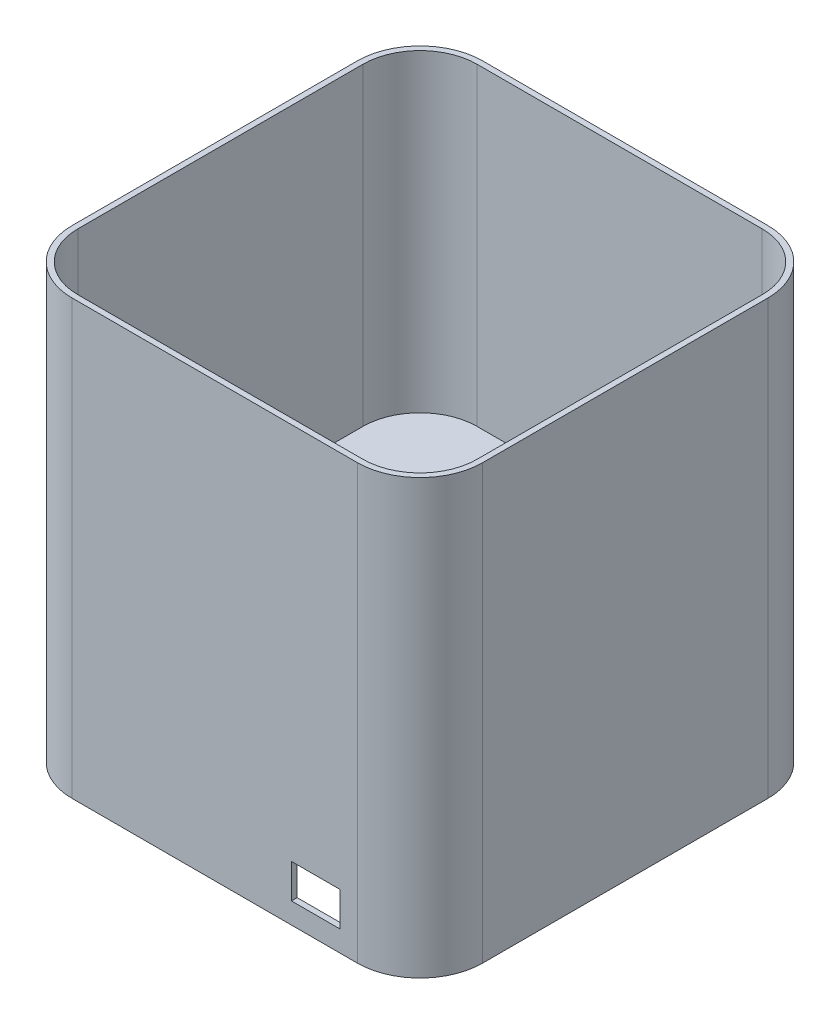
SolidWorks part; units mm, degrees
ref_plane "Plan de face" through (0, 0, 0) normal (0, 0, 1) x (1, 0, 0)
ref_plane "Plan de dessus" through (0, 0, 0) normal (0, 1, 0) x (1, 0, 0)
ref_plane "Plan de droite" through (0, 0, 0) normal (1, 0, 0) x (0, 0, -1)
sketch "Esquisse1" plane through (0, 0, 0) normal (0, 1, 0) x (1, 0, 0)
  line L30 (-70, -70) -> (70, -70)
  line L31 (-70, -70) -> (-70, 70)
  line L32 (-70, 70) -> (70, 70)
  line L33 (70, -70) -> (70, 70)
  line L34 (-70, -70) -> (70, 70) construction
  line L35 (-70, 70) -> (70, -70) construction
  point P0 (0, 0)
  dimension "D1" = 140
  dimension "D2" = 140
extrude "Boss.-Extru.1" add sketch "Esquisse1" along normal blind 150
fillet "Congé1" radius 20 4 edges at (70, 75, 70) (-70, 75, 70) (-70, 75, -70) (70, 75, -70)
shell "Coque1" thickness 2
sketch "Esquisse2" plane through (0, 0, 0) normal (0, 1, 0) x (1, 0, 0)
  line L4 (70, -50) -> (70, 50)
  line L5 (50, 70) -> (-50, 70)
  line L6 (-70, 50) -> (-70, -50)
  line L7 (-50, -70) -> (50, -70)
  line L8 (70, -50) -> (70, 50)
  line L9 (50, 70) -> (-50, 70)
  line L10 (-70, 50) -> (-70, -50)
  line L11 (-50, -70) -> (50, -70)
  arc A4 (70, 50) -> (50, 70) centre (50, 50) ccw
  arc A5 (70, 50) -> (50, 70) centre (50, 50) ccw
  arc A6 (-50, 70) -> (-70, 50) centre (-50, 50) ccw
  arc A7 (-50, 70) -> (-70, 50) centre (-50, 50) ccw
  arc A8 (-70, -50) -> (-50, -70) centre (-50, -50) ccw
  arc A9 (-70, -50) -> (-50, -70) centre (-50, -50) ccw
  arc A10 (50, -70) -> (70, -50) centre (50, -50) ccw
  arc A11 (50, -70) -> (70, -50) centre (50, -50) ccw
  dimension "D1" = 0
extrude "Boss.-Extru.2" add sketch "Esquisse2" along normal blind 40
sketch "Esquisse3" plane through (0, -2, 0) normal (0, -1, 0) x (1, 0, 0)
  line L8 (70, -50) -> (70, 50)
  line L9 (50, 70) -> (-50, 70)
  line L10 (-70, 50) -> (-70, -50)
  line L11 (-50, -70) -> (50, -70)
  line L12 (70, -50) -> (70, 50)
  line L13 (50, 70) -> (-50, 70)
  line L14 (-70, 50) -> (-70, -50)
  line L15 (-50, -70) -> (50, -70)
  arc A4 (70, 50) -> (50, 70) centre (50, 50) ccw
  arc A5 (70, 50) -> (50, 70) centre (50, 50) ccw
  arc A6 (-50, 70) -> (-70, 50) centre (-50, 50) ccw
  arc A7 (-50, 70) -> (-70, 50) centre (-50, 50) ccw
  arc A8 (-70, -50) -> (-50, -70) centre (-50, -50) ccw
  arc A9 (-70, -50) -> (-50, -70) centre (-50, -50) ccw
  arc A10 (50, -70) -> (70, -50) centre (50, -50) ccw
  arc A11 (50, -70) -> (70, -50) centre (50, -50) ccw
  dimension "D1" = 2
extrude "Enlèv. mat.-Extru.1" cut sketch "Esquisse3" against normal blind 38
sketch "Esquisse4" plane through (0, 36, 0) normal (0, -1, 0) x (1, 0, 0)
  line L0 (0, 34.9414) -> (0, 0) construction
  line L1 (-11.5, 35.9414) -> (11.5, 35.9414)
  line L2 (-11.5, 35.9414) -> (-11.5, 33.9414)
  line L3 (-11.5, 33.9414) -> (11.5, 33.9414)
  line L4 (11.5, 35.9414) -> (11.5, 33.9414)
  line L5 (-11.5, 35.9414) -> (11.5, 33.9414) construction
  line L6 (-11.5, 33.9414) -> (11.5, 35.9414) construction
  point P0 (0, 34.9414)
  point P8 (0, 34.9414)
  dimension "D1" = 23
  dimension "D2" = 2
extrude "Enlèv. mat.-Extru.2" cut sketch "Esquisse4" against normal blind 33
sketch "Esquisse5" plane through (0, 0, -72) normal (0, 0, -1) x (-1, 0, 0)
  line L0 (0, 0) -> (0, 16.5) construction
  line L1 (-35, 28.5) -> (35, 28.5)
  line L2 (-35, 28.5) -> (-35, 4.5)
  line L3 (-35, 4.5) -> (35, 4.5)
  line L4 (35, 28.5) -> (35, 4.5)
  line L5 (-35, 28.5) -> (35, 4.5) construction
  line L6 (-35, 4.5) -> (35, 28.5) construction
  line L8 (-50, 36) -> (50, 36) construction
  point P0 (0, 16.5)
  dimension "D1" = 70
  dimension "D2" = 24
  dimension "D3" = 7.5
extrude "Enlèv. mat.-Extru.3" cut sketch "Esquisse5" against normal blind 33
sketch "Esquisse6" plane through (0, 0, 72) normal (0, 0, 1) x (1, 0, 0)
  line L1 (26.9193, 17.3386) -> (43.9193, 17.3386)
  line L2 (26.9193, 17.3386) -> (26.9193, 5.3386)
  line L3 (26.9193, 5.3386) -> (43.9193, 5.3386)
  line L4 (43.9193, 17.3386) -> (43.9193, 5.3386)
  dimension "D1" = 17
  dimension "D2" = 12
extrude "Enlèv. mat.-Extru.4" cut sketch "Esquisse6" against normal blind 33
sketch "Esquisse7" plane through (11.5, 0, 0) normal (-1, 0, 0) x (0, 0, 1)
  line L0 (33.9414, 40) -> (34.8414, 40)
  line L3 (34.8414, 40) -> (34.8414, 39.8568)
  line L4 (34.8414, 39.8568) -> (33.9414, 39.75)
  line L5 (33.9414, 40) -> (33.9414, 36) construction
  line L6 (33.9414, 39.75) -> (33.9414, 40)
  line L7 (-50, 40) -> (50, 40) construction
  point P2 (0, 0)
  point P9 (33.9414, 40)
  point P10 (33.9414, 39.4523)
  point P11 (34.8414, 39.8568)
  dimension "D1" = 0.9
  dimension "D2" = 0.25
extrude "Boss.-Extru.3" add sketch "Esquisse7" along normal up to surface (23 mm away) up to face at (-11.5, 38, 34.9414)
sketch "Esquisse10" plane through (-11.5, 0, 0) normal (1, 0, 0) x (0, 0, -1)
  line L0 (-35.9414, 40) -> (-35.0414, 40)
  line L1 (-50, 40) -> (50, 40) construction
  line L2 (-35.0414, 40) -> (-35.0414, 39.8854)
  line L3 (-35.0414, 39.8854) -> (-35.9414, 39.75)
  line L4 (-35.9414, 40) -> (-35.9414, 36) construction
  line L5 (-35.9414, 39.75) -> (-35.9414, 40)
  line L7 (-50, 40) -> (50, 40) construction
  point P9 (-35.9414, 34.9057)
  point P11 (-35.9414, 39.6424)
  point P13 (-34.8874, 34.9057)
  point P14 (-35.0854, 40)
  point P17 (0, 0)
  point P18 (-34.9774, 39.8044)
  point P19 (-35.0414, 39.8854)
  dimension "D1" = 0.25
  dimension "D2" = 0.9
extrude "Boss.-Extru.4" add sketch "Esquisse10" along normal up to surface (23 mm away) up to face at (11.5, 38.6011, 34.908)
sketch "Esquisse12" plane through (0, 0, 70) normal (0, 0, -1) x (-1, 0, 0)
  circle A0 centre (28.0439, 18.4765) radius 1.475
  dimension "D1" = 2.95
extrude "Boss.-Extru.5" add sketch "Esquisse12" along normal blind 3
